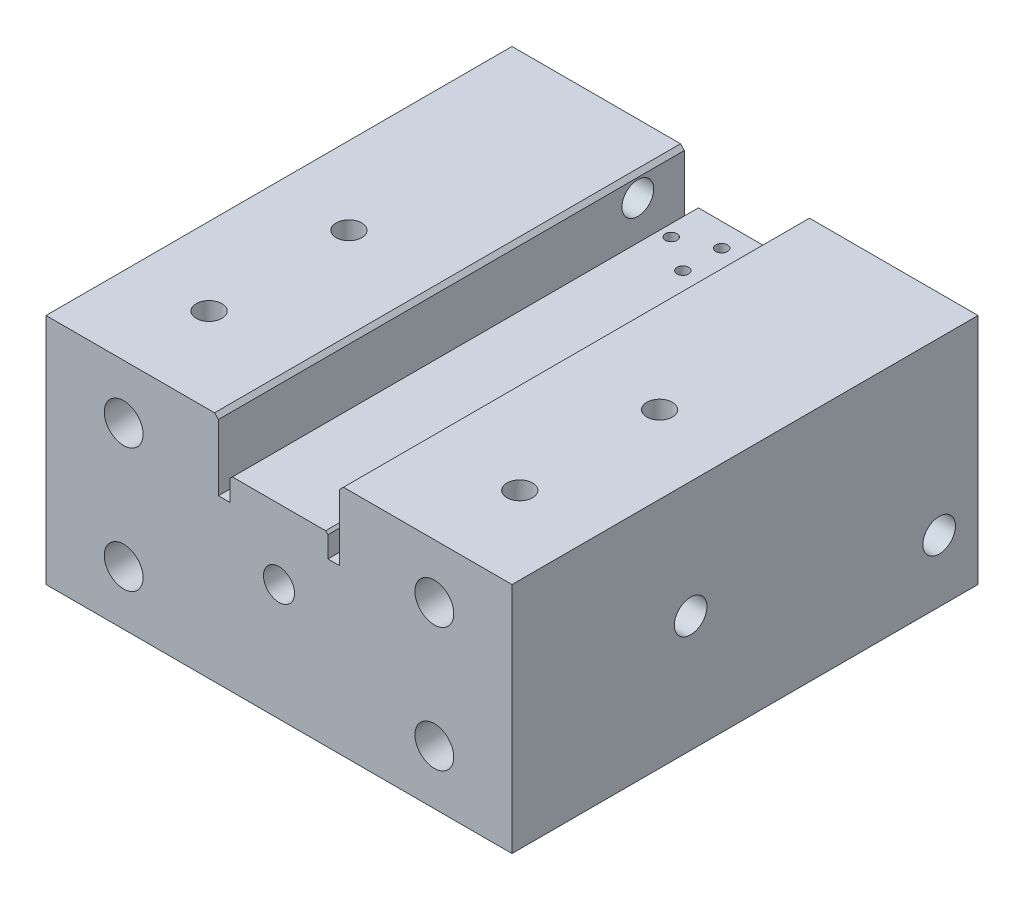
SolidWorks part; units mm, degrees
material "SKD11淬火HRC56-60"
ref_plane "前基準面" through (0, 0, 0) normal (0, 0, 1) x (1, 0, 0)
ref_plane "上基準面" through (0, 0, 0) normal (0, 1, 0) x (1, 0, 0)
ref_plane "右基準面" through (0, 0, 0) normal (1, 0, 0) x (0, 0, -1)
sketch "草图1" plane through (0, 0, 0) normal (0, 0, 1) x (1, 0, 0)
  line L1 (0, 0) -> (60, 0)
  line L2 (0, 0) -> (0, 30)
  line L3 (0, 30) -> (60, 30)
  line L4 (60, 0) -> (60, 30)
  dimension "D1" = 30
  dimension "D2" = 60
extrude "凸台-拉伸1" add sketch "草图1" along normal blind 60
sketch "草图2" plane through (0, 0, 0) normal (0, 0, -1) x (-1, 0, 0)
  line L0 (-60, 30) -> (0, 30) construction
  line L1 (-22.2, 30) -> (-37.8, 30)
  line L2 (-22.2, 30) -> (-22.2, 24)
  line L3 (-22.2, 24) -> (-37.8, 24)
  line L4 (-37.8, 30) -> (-37.8, 24)
  line L5 (-30, 30) -> (-30, 23.2081) construction
  dimension "D1" = 6
  dimension "D2" = 15.6
extrude "切除-拉伸1" cut sketch "草图2" against normal through all
sketch "草图3" plane through (0, 0, 0) normal (0, 0, -1) x (-1, 0, 0)
  line L0 (-30, 24) -> (-30, 27.5917) construction
  line L1 (-37.8, 24) -> (-36.3, 24)
  line L2 (-37.8, 24) -> (-37.8, 21)
  line L3 (-37.8, 21) -> (-36.3, 21)
  line L4 (-36.3, 24) -> (-36.3, 21)
  line L5 (-37.8, 24) -> (-22.2, 24) construction
  line L6 (-23.7, 24) -> (-23.7, 21)
  line L7 (-22.2, 21) -> (-23.7, 21)
  line L8 (-22.2, 24) -> (-22.2, 21)
  line L9 (-22.2, 24) -> (-23.7, 24)
  dimension "D1" = 1.5
  dimension "D2" = 3
extrude "切除-拉伸2" cut sketch "草图3" against normal through all
chamfer "倒角1" distance 0.3 angle 45 2 edges at (23.7, 24, 30) (36.3, 24, 30)
chamfer "倒角2" distance 0.5 angle 45 2 edges at (22.2, 30, 30) (37.8, 30, 30)
hole_wizard "M6 螺纹孔1" positions "草图5" profile "草图4" tap size "M6" standard "ISO"
sketch "草图5" plane through (0, 0, 60) normal (0, 0, 1) x (1, 0, 0)
  line L0 (30, 0) -> (30, 24) construction
  line L1 (0, 0) -> (60, 0) construction
  line L2 (36, 24) -> (24, 24) construction
  line L3 (0, 15) -> (60, 15) construction
  line L4 (0, 30) -> (0, 0) construction
  line L5 (60, 0) -> (60, 30) construction
  point P0 (10, 23)
  point P1 (50, 23)
  point P3 (50, 7)
  point P5 (10, 7)
  dimension "D1" = 16
  dimension "D2" = 40
sketch "草图4" plane through (10, 23, 60) normal (1, 0, 0) x (0, -1, 0)
  line L0 (0, 0) -> (0, 16.5022)
  line L1 (0, 16.5022) -> (2.5, 15)
  line L2 (2.5, 15) -> (2.5, 0)
  line L5 (2.5, 0) -> (0, 0)
  line L10 (0, 16.5022) -> (-2.5, 15) construction
  line L11 (0, -6.35) -> (0, 107.95) construction
  dimension "螺纹孔钻头直径" = 5
  dimension "螺纹孔钻头深度" = 15
  dimension "导头角度" = 118
cosmetic thread "孔螺蚊线1" parameters "D1"=12, "D2"=6
cosmetic thread "孔螺蚊线2" parameters "D1"=12, "D2"=6
cosmetic thread "孔螺蚊线3" parameters "D1"=12, "D2"=6
cosmetic thread "孔螺蚊线4" parameters "D1"=12, "D2"=6
sketch "草图6" plane through (0, 0, 0) normal (-1, 0, 0) x (0, 0, 1)
  line L0 (0, 30) -> (0, 0) construction
  line L1 (60, 30) -> (0, 30) construction
  circle A0 centre (6, 27.2) radius 2.05
  dimension "D1" = 4.1
  dimension "D2" = 6
  dimension "D3" = 2.8
extrude "切除-拉伸3" cut sketch "草图6" against normal up to surface (22.2 mm away) up to face at (22.2, 25.25, 30)
hole_wizard "Ø6.0 (6) 直径孔1" positions "草图8" profile "草图9" hole size "Ø6.0" standard "ISO"
sketch "草图8" plane through (0, 0, 60) normal (0, 0, 1) x (1, 0, 0)
  line L2 (60, 15) -> (0, 15) construction
  line L3 (60, 0) -> (60, 30) construction
  line L4 (0, 30) -> (0, 0) construction
  point P0 (30, 15)
sketch "草图9" plane through (30, 15, 60) normal (1, 0, 0) x (0, -1, 0)
  line L0 (0, 0) -> (0, 59.2017)
  line L1 (0, 59.2017) -> (2, 58)
  line L2 (2, 58) -> (2, 0)
  line L5 (2, 0) -> (0, 0)
  line L10 (0, 59.2017) -> (-2, 58) construction
  line L11 (0, -6.35) -> (0, 107.95) construction
  dimension "孔直径" = 4
  dimension "孔深度" = 58
  dimension "导头角度" = 118
hole_wizard "M5 螺纹孔1" positions "草图11" profile "草图10" tap size "M5" standard "ISO"
sketch "草图11" plane through (60, 0, 0) normal (1, 0, 0) x (0, 0, -1)
  line L0 (-60, 15) -> (-21.8071, 15) construction
  line L1 (-60, 0) -> (-60, 30) construction
  point P0 (-37, 15)
  dimension "D1" = 23
sketch "草图10" plane through (60, 15, 37) normal (0, 1, 0) x (0, 0, -1)
  line L0 (0, 0) -> (0, 13.6618)
  line L1 (0, 13.6618) -> (2.1, 12.4)
  line L2 (2.1, 12.4) -> (2.1, 0)
  line L5 (2.1, 0) -> (0, 0)
  line L10 (0, 13.6618) -> (-2.1, 12.4) construction
  line L11 (0, -6.35) -> (0, 107.95) construction
  dimension "螺纹孔钻头直径" = 4.2
  dimension "螺纹孔钻头深度" = 12.4
  dimension "导头角度" = 118
cosmetic thread "孔螺蚊线5" parameters "D1"=10, "D2"=5
sketch "草图12" plane through (60, 0, 0) normal (1, 0, 0) x (0, 0, -1)
  circle A0 centre (-37, 15) radius 2
  dimension "D1" = 4
extrude "切除-拉伸4" cut sketch "草图12" against normal blind 33
sketch "草图13" plane through (0, 24, 0) normal (0, 1, 0) x (1, 0, 0)
  line L0 (30, 0) -> (30, -19.082) construction
  line L1 (36, 0) -> (24, 0) construction
  circle A0 centre (30, -3) radius 0.75
  circle A1 centre (30, -8) radius 0.75
  dimension "D1" = 1.5
  dimension "D2" = 3
  dimension "D3" = 8
extrude "切除-拉伸5" cut sketch "草图13" against normal blind 10
hole_wizard "M5 螺纹孔2" positions "草图15" profile "草图14" tap size "M5" standard "ISO"
sketch "草图15" plane through (60, 0, 0) normal (1, 0, 0) x (0, 0, -1)
  line L0 (0, 0) -> (0, 30) construction
  line L1 (-60, 0) -> (0, 0) construction
  point P0 (-5, 8)
  dimension "D1" = 5
  dimension "D2" = 8
sketch "草图14" plane through (60, 8, 5) normal (0, 1, 0) x (0, 0, -1)
  line L0 (0, 0) -> (0, 13.6618)
  line L1 (0, 13.6618) -> (2.1, 12.4)
  line L2 (2.1, 12.4) -> (2.1, 0)
  line L5 (2.1, 0) -> (0, 0)
  line L10 (0, 13.6618) -> (-2.1, 12.4) construction
  line L11 (0, -6.35) -> (0, 107.95) construction
  dimension "螺纹孔钻头直径" = 4.2
  dimension "螺纹孔钻头深度" = 12.4
  dimension "导头角度" = 118
cosmetic thread "孔螺蚊线6" parameters "D1"=10, "D2"=5
sketch "草图16" plane through (60, 0, 0) normal (1, 0, 0) x (0, 0, -1)
  circle A0 centre (-5, 8) radius 2
  dimension "D1" = 4
extrude "切除-拉伸6" cut sketch "草图16" against normal blind 40
sketch "草图17" plane through (0, 24, 0) normal (0, 1, 0) x (1, 0, 0)
  line L0 (30, 0) -> (30, -10.5138) construction
  line L1 (36, 0) -> (24, 0) construction
  circle A0 centre (25.5, -5) radius 0.75
  circle A1 centre (34.5, -5) radius 0.75
  dimension "D1" = 1.5
  dimension "D2" = 9
  dimension "D3" = 5
extrude "切除-拉伸7" cut sketch "草图17" against normal blind 15
hole_wizard "M4 螺纹孔1" positions "草图19" profile "草图18" tap size "M4" standard "ISO"
sketch "草图19" plane through (0, 0, 0) normal (0, 0, -1) x (-1, 0, 0)
  point P1 (-53, 25)
  point P4 (-53, 15)
  point P7 (-7, 15)
  point P10 (-7, 25)
sketch "草图18" plane through (53, 25, 0) normal (1, 0, 0) x (0, 1, 0)
  line L0 (0, 0) -> (0, 11.0914)
  line L1 (0, 11.0914) -> (1.65, 10.1)
  line L2 (1.65, 10.1) -> (1.65, 0)
  line L5 (1.65, 0) -> (0, 0)
  line L10 (0, 11.0914) -> (-1.65, 10.1) construction
  line L11 (0, -6.35) -> (0, 107.95) construction
  dimension "螺纹孔钻头直径" = 3.3
  dimension "螺纹孔钻头深度" = 10.1
  dimension "导头角度" = 118
cosmetic thread "孔螺蚊线7" parameters "D1"=8, "D2"=4
cosmetic thread "孔螺蚊线8" parameters "D1"=8, "D2"=4
cosmetic thread "孔螺蚊线9" parameters "D1"=8, "D2"=4
cosmetic thread "孔螺蚊线10" parameters "D1"=8, "D2"=4
hole_wizard "M4 螺纹孔2" positions "草图21" profile "草图20" tap size "M4" standard "ISO"
sketch "草图21" plane through (0, 30, 0) normal (0, 1, 0) x (-1, 0, 0)
  point P0 (-50, 31)
  point P1 (-50, 49)
  point P4 (-10, 49)
  point P7 (-10, 31)
sketch "草图20" plane through (50, 30, 31) normal (1, 0, 0) x (0, 0, 1)
  line L0 (0, 0) -> (0, 11.0914)
  line L1 (0, 11.0914) -> (1.65, 10.1)
  line L2 (1.65, 10.1) -> (1.65, 0)
  line L5 (1.65, 0) -> (0, 0)
  line L10 (0, 11.0914) -> (-1.65, 10.1) construction
  line L11 (0, -6.35) -> (0, 107.95) construction
  dimension "螺纹孔钻头直径" = 3.3
  dimension "螺纹孔钻头深度" = 10.1
  dimension "导头角度" = 118
cosmetic thread "孔螺蚊线12" parameters "D1"=8, "D2"=4
cosmetic thread "孔螺蚊线13" parameters "D1"=8, "D2"=4
cosmetic thread "孔螺蚊线14" parameters "D1"=8, "D2"=4
cosmetic thread "孔螺蚊线15" parameters "D1"=8, "D2"=4
